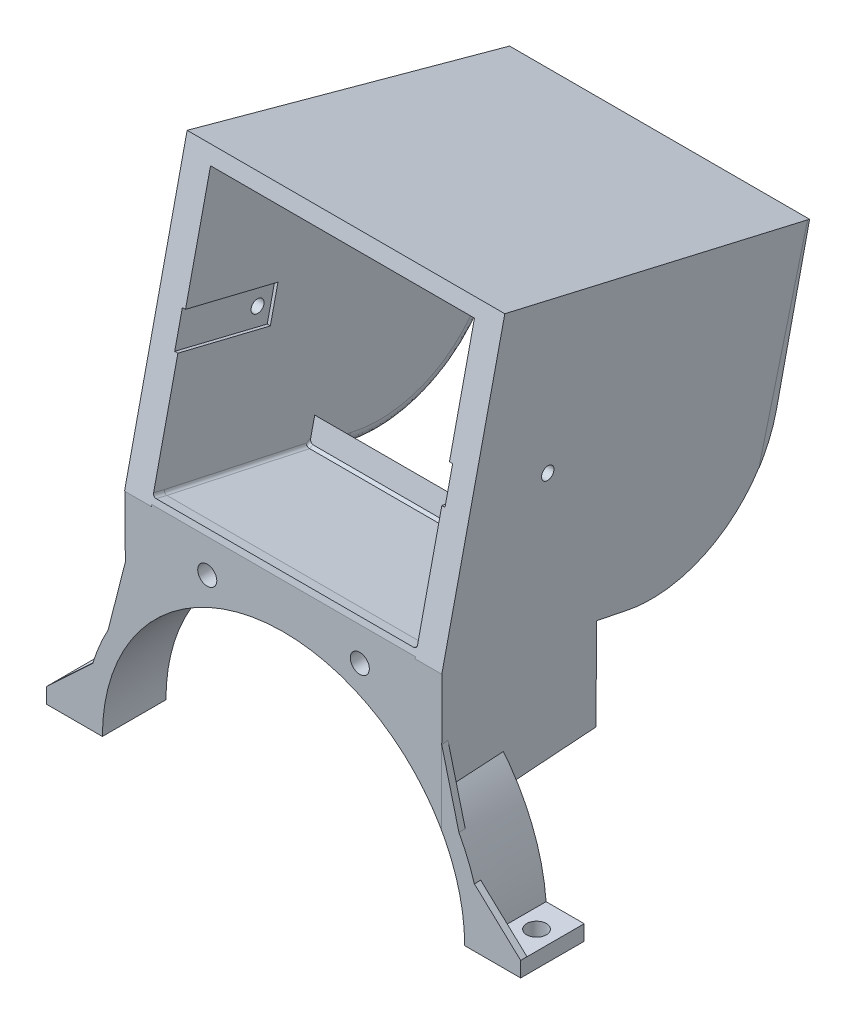
SolidWorks part; units mm, degrees
ref_plane "Front Plane" through (0, 0, 0) normal (0, 0, 1) x (1, 0, 0)
ref_plane "Top Plane" through (0, 0, 0) normal (0, 1, 0) x (1, 0, 0)
ref_plane "Right Plane" through (0, 0, 0) normal (1, 0, 0) x (0, 0, -1)
sketch "base" plane through (0, 0, 0) normal (0, 0, 1) x (1, 0, 0)
  line L0 (0, 36.3204) -> (0, -41.5291) construction
  line L2 (-31.5824, 35.5) -> (36.4866, 35.5) construction
  line L5 (0, 35.5) -> (25, 35.5)
  line L6 (25, 35.5) -> (25, 13.6839)
  line L7 (0, 35.5) -> (0, 28.5)
  circle A0 centre (0, 0) radius 28.5 construction
  circle A1 centre (12, 30.225) radius 1.5
  arc A3 (25, 13.6839) -> (0, 28.5) centre (0, 0) ccw
  point P3 (0, 35.5)
  point P7 (0, 28.5)
  point P8 (0, 31.5)
  dimension "D1" = 57
  dimension "D6" = 3
  dimension "D2" = 25
  dimension "D4" = 3
  dimension "D5" = 7
  dimension "D7" = 5.275
  dimension "D8" = 12
extrude "Boss-Extrude1" add sketch "base" along normal blind 25
sketch "cam" plane through (0, 0, 0) normal (-1, 0, 0) x (0, 0, 1)
  line L0 (0.844, 31.725) -> (23.1356, 36.0581) construction
  line L1 (25, 31.725) -> (0, 31.725) construction
  line L2 (23.1356, 36.0581) -> (14.0658, 76.6265) construction
  line L3 (14.0658, 76.6265) -> (-7.9488, 71.0541) construction
  line L4 (-7.9488, 71.0541) -> (0.844, 31.725) construction
  line L5 (-3.5524, 51.3895) -> (18.6007, 56.3423) construction
  point P8 (0, 35.5)
  dimension "D1" = 22.7
  dimension "D2" = 41.57
  dimension "D3" = 40.3
  dimension "D4" = 11
  dimension "D5" = 0
sketch "Sketch1" plane through (0, 0, 0) normal (-1, 0, 0) x (0, 0, 1)
  line L0 (25, 35.5) -> (24.7924, 36.4285)
  line L1 (15.1771, 79.4367) -> (-34.1616, 66.9478)
  line L3 (-27.1308, 35.5) -> (25, 35.5) construction
  line L4 (23.1356, 36.0581) -> (14.0658, 76.6265) construction
  line L5 (14.0658, 76.6265) -> (-7.9488, 71.0541) construction
  line L6 (-34.1616, 66.9478) -> (-27.1308, 35.5) construction
  line L7 (-7.9488, 71.0541) -> (0.844, 31.725) construction
  line L9 (23.1356, 36.0581) -> (20.2647, 35.5)
  line L10 (0.844, 31.725) -> (23.1356, 36.0581) construction
  line L11 (20.2647, 35.5) -> (25, 35.5)
  line L12 (14.0658, 76.6265) -> (-33.6265, 64.5544)
  line L13 (-33.6265, 64.5544) -> (-34.1616, 66.9478)
  line L14 (14.0658, 76.6265) -> (15.7225, 76.997)
  line L15 (23.1356, 36.0581) -> (24.7924, 36.4285)
  line L16 (15.7225, 76.997) -> (15.1771, 79.4367)
  dimension "D1" = 2.5
extrude "Boss-Extrude2" add sketch "Sketch1" against normal blind 22
sketch "Sketch2" plane through (0, 0, 0) normal (-1, 0, 0) x (0, 0, 1)
  line L0 (0, 35.5) -> (0.7654, 32.0766)
  line L1 (-7.9488, 71.0541) -> (0.844, 31.725) construction
  line L2 (0.7654, 32.0766) -> (1.2877, 31.8113)
  line L3 (0.844, 31.725) -> (23.1356, 36.0581) construction
  line L4 (1.2877, 31.8113) -> (20.2647, 35.5)
  line L5 (20.2647, 35.5) -> (0, 35.5)
extrude "Cut-Extrude1" cut sketch "Sketch2" against normal blind 22.5
ref_plane "Plane1" through (0, 49.6996, -11.1113) normal (0, -0.9759, 0.2182) x (0, 0.2182, 0.9759)
sketch "Sketch6" plane through (0, 49.6996, -11.1113) normal (0, -0.9759, 0.2182) x (0, 0.2182, 0.9759)
  line L0 (30.6159, 0) -> (30.6159, -20.72) construction
  line L1 (30.6159, -20.72) -> (9.8248, -20.15) construction
  line L2 (9.8248, -20.15) -> (9.8248, 0) construction
  line L3 (7.7455, 0) -> (30.4455, 0) construction
  line L4 (9.8248, 0) -> (30.6159, 0) construction
  line L6 (-18.7317, -22) -> (-18.7317, 0) construction
  line L8 (-18.7317, -19.3671) -> (30.6159, -20.72)
  line L10 (32.1432, -25) -> (-18.7317, -23.6052)
  line L11 (-18.7317, -23.6052) -> (-18.7317, -19.3671)
  line L13 (30.6159, -20.72) -> (32.1432, -20.7619)
  line L14 (32.1432, -22) -> (32.1432, 0) construction
  line L15 (32.1432, -20.7619) -> (32.1432, -25)
  ellipse E0 centre (24.3977, 0) end of major axis (24.3977, 28.5) minor radius 6.2182 (27.3833, -25) -> (30.6159, 0) ccw construction
  point P15 (0, 0)
  point P23 (0, 0)
  point P24 (0, 0)
  dimension "D1" = 20.15
  dimension "D2" = 20.72
  dimension "D3" = 4.2365
extrude "Boss-Extrude3" add sketch "Sketch6" against normal blind 33 and the other way blind 22
sketch "Sketch22" plane through (19.8657, -0.1188, -0.5315) normal (-0.9996, 0.006, 0.0267) x (0.0267, -0.0002, 0.9996)
  line L1 (-29.043, 45.6891) -> (6.8124, 53.7083) construction
  line L2 (25.333, 36.552) -> (13.5938, 89.0403) construction
  line L3 (20.1962, 59.5196) -> (6.0458, 56.3548)
  line L4 (6.0458, 56.3548) -> (6.646, 53.6711)
  line L5 (6.646, 53.6711) -> (20.7964, 56.8359)
  line L6 (20.1962, 59.5196) -> (20.3152, 59.5196)
  line L7 (25.654, 35.6489) -> (13.7072, 89.0656) construction
  line L8 (20.3152, 59.5196) -> (20.9098, 56.8612)
  line L9 (20.9098, 56.8612) -> (20.7964, 56.8359)
  dimension "D1" = 2.75
  dimension "D2" = 14.5
extrude "Cut-Extrude11" cut sketch "Sketch22" against normal blind 0.5
mirror "Mirror2" about plane through (20.8643, 53.5473, 6.0988) normal (0, -0.9759, 0.2182) of "Cut-Extrude11"
sketch "Sketch23" plane through (19.8657, -0.1188, -0.5315) normal (-0.9996, 0.006, 0.0267) x (0.0267, -0.0002, 0.9996)
  line L0 (-3.5594, 51.3886) -> (18.585, 56.3413) construction
  line L1 (20.2103, 59.5196) -> (21.4094, 54.1582) construction
  circle A0 centre (8.7088, 54.1324) radius 1
  dimension "D1" = 2
  dimension "D2" = 12.4
extrude "Cut-Extrude12" cut sketch "Sketch23" against normal through all
sketch "Sketch28" plane through (0, 71.0431, -17.9829) normal (0, 0.9694, -0.2454) x (1, 0, 0)
  line L0 (25, -34.4774) -> (28.6999, -1.5706)
  line L1 (28.6999, -1.5706) -> (23.6052, 16.3776)
  line L2 (23.6052, 16.3776) -> (25, -34.4774)
extrude "Cut-Extrude15" cut sketch "Sketch28" against normal through all
sketch "Sketch29" plane through (0, 0, 0) normal (-1, 0, 0) x (0, 0, 1)
  line L0 (-34.1616, 66.9478) -> (-36.5918, 77.8176)
  line L1 (-36.5918, 77.8176) -> (13.0574, 88.9177)
  line L2 (13.0574, 88.9177) -> (15.1771, 79.4367)
  line L3 (15.1771, 79.4367) -> (-34.1616, 66.9478)
extrude "Cut-Extrude16" cut sketch "Sketch29" against normal through all
sketch "Sketch33" plane through (0, 0, 25) normal (0, 0, 1) x (1, 0, 0)
  line L1 (28.5, 0) -> (31.5, 0)
  line L3 (31.5, 0) -> (37.3081, 0)
  line L4 (37.3081, 0) -> (37.3081, 2.4)
  line L5 (37.3081, 2.4) -> (31.3081, 2.4)
  line L6 (20.3682, 19.9346) -> (22.4407, 21.963)
  arc A1 (22.4407, 21.963) -> (31.3081, 2.4) centre (0, 0) cw
  arc A2 (24.8135, 14.0194) -> (0, 28.5) centre (0, 0) ccw construction
  arc A3 (20.3682, 19.9346) -> (28.5, 0) centre (0, 0) cw
  dimension "D1" = 31.4
  dimension "D2" = 6
  dimension "D3" = 2.4
extrude "Boss-Extrude5" add sketch "Sketch33" against normal blind 10 separate body
sketch "Sketch35" plane through (0, 0, 25) normal (0, 0, 1) x (1, 0, 0)
  line L0 (37.3081, 2.4) -> (30.0258, 2.4)
  line L1 (30.0258, 2.4) -> (30.0258, 9.1876)
  line L2 (30.0258, 9.1876) -> (37.3081, 2.4)
  line L3 (27.7385, 14.4151) -> (24.5274, 27.0009)
  line L4 (24.5274, 27.0009) -> (24.2322, 17.9214)
  line L5 (24.2322, 17.9214) -> (27.7385, 14.4151)
  arc A0 (31.3081, 2.4) -> (22.4407, 21.963) centre (0, 0) ccw construction
  point P9 (0, 0)
extrude "Boss-Extrude6" add sketch "Sketch35" against normal blind 1
sketch "Sketch34" plane through (0, 2.4, 0) normal (0, 1, 0) x (1, 0, 0)
  line L0 (37.3081, -19.5) -> (33.9446, -19.5) construction
  line L1 (37.3081, -15) -> (37.3081, -24) construction
  line L2 (34.3081, -25) -> (34.3081, -19.5) construction
  line L3 (37.3081, -25) -> (31.3081, -25) construction
  circle A0 centre (34.3081, -19.5) radius 1.55
extrude "Cut-Extrude18" cut sketch "Sketch34" against normal through all
fillet "Fillet13" radius 20 1 edges at (21.4862, 24.1427, -24.5917)
fillet "Fillet14" radius 2 3 edges at (19.3671, 55.3043, -31.5585) (19.9867, 29.0735, -2.5368) (19.5277, 31.1375, -20.1531)
fillet "Fillet17" radius 0.5 3 edges at (20.0992, 31.9439, 1.0265) (20.7386, 36.2433, 23.964) (20.4104, 33.9347, 12.2117)
mirror "Mirror42" about plane through (0, 35.5, 25) normal (1, 0, 0) of "Boss-Extrude6", "Boss-Extrude2", "Cut-Extrude1", "Boss-Extrude1", "Boss-Extrude3", "Cut-Extrude11", "Mirror2", "Cut-Extrude12", "Cut-Extrude15", "Cut-Extrude16", "Fillet13", "Fillet14", "Fillet17", "Boss-Extrude5", "Cut-Extrude18"
